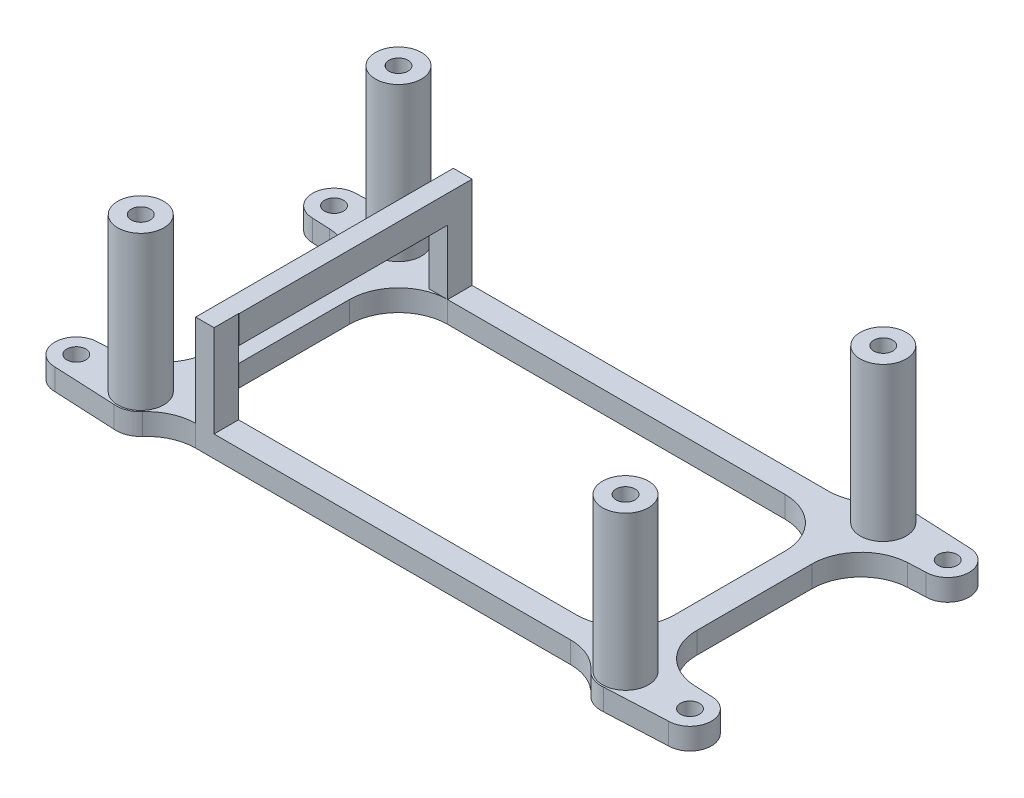
SolidWorks part; units mm, degrees
ref_plane "Front Plane" through (0, 0, 0) normal (0, 0, 1) x (1, 0, 0)
ref_plane "Top Plane" through (0, 0, 0) normal (0, 1, 0) x (1, 0, 0)
ref_plane "Right Plane" through (0, 0, 0) normal (1, 0, 0) x (0, 0, -1)
sketch "Sketch10" plane through (0, 0, 0) normal (0, 1, 0) x (1, 0, 0)
  line L0 (39.5, 0) -> (39.5, -21) construction
  line L1 (0, 0) -> (79, 0)
  line L2 (0, 0) -> (0, -42)
  line L3 (0, -42) -> (79, -42)
  line L4 (79, 0) -> (79, -42)
  line L5 (4, -38) -> (75, -38)
  line L6 (4, -38) -> (4, -4)
  line L7 (4, -4) -> (75, -4)
  line L8 (75, -38) -> (75, -4)
  line L9 (4, -38) -> (75, -4) construction
  line L10 (4, -4) -> (75, -38) construction
  line L11 (-10.5, 3.5) -> (0, 4)
  line L12 (-10.5, -3.5) -> (0, -4)
  line L13 (-10.5, -38.5) -> (0, -38)
  line L14 (-10.5, -45.5) -> (0, -46)
  line L15 (89.5, 3.5) -> (79, 4)
  line L16 (89.5, -3.5) -> (79, -4)
  line L17 (89.5, -38.5) -> (79, -38)
  line L18 (89.5, -45.5) -> (79, -46)
  circle A0 centre (0, 0) radius 4
  circle A1 centre (79, 0) radius 4
  circle A2 centre (79, -42) radius 4
  circle A3 centre (0, -42) radius 4
  circle A4 centre (-10.5, 0) radius 3.5
  circle A5 centre (-10.5, -42) radius 3.5
  circle A6 centre (89.5, 0) radius 3.5
  circle A7 centre (89.5, -42) radius 3.5
  arc A8 (-10.5, 3.5) -> (-10.5, -3.5) centre (-10.5, 0) cw
  arc A9 (0, 4) -> (0, -4) centre (0, 0) ccw
  arc A10 (79, 4) -> (79, -4) centre (79, 0) cw
  arc A11 (79, -38) -> (79, -46) centre (79, -42) cw
  arc A12 (89.5, -38.5) -> (89.5, -45.5) centre (89.5, -42) ccw
  arc A13 (0, -38) -> (0, -46) centre (0, -42) ccw
  arc A14 (-10.5, -38.5) -> (-10.5, -45.5) centre (-10.5, -42) cw
  point P5 (39.5, -21)
  point P10 (39.5, 0)
  point P11 (0, -21)
  dimension "D3" = 79
  dimension "D4" = 42
  dimension "D5" = 8
  dimension "D6" = 7
  dimension "D1" = 4
  dimension "D2" = 4
  dimension "D7" = 100
extrude "Boss-Extrude6" add sketch "Sketch10" along normal blind 3.5 contours A3 L3 A2 L4 A1 L1 A0 L2 L8 L5 L6 L7 | L1 A0 L11 L12 L2 | L2 A0 L1 | L3 A3 L2 | L1 A1 L4 | L18 A2 L17 L4 L3 | L16 A1 L15 L1 L4 | A5 L14 A3 L13 | A5 | A7 | A7 L17 A2 L18 | L4 A2 L3 | A6 | A6 L15 A1 L16 | A4 L12 A0 L11 | A4
sketch "Sketch11" plane through (0, 3.5, 0) normal (0, 1, 0) x (1, 0, 0)
  circle A0 centre (0, 0) radius 1.55
  circle A1 centre (79, 0) radius 1.55
  circle A2 centre (79, -42) radius 1.55
  circle A3 centre (0, -42) radius 1.55
  circle A4 centre (-10.5, -42) radius 1.55
  circle A5 centre (-10.5, 0) radius 1.55
  circle A6 centre (89.5, 0) radius 1.55
  circle A7 centre (89.5, -42) radius 1.55
  dimension "D1" = 3.1
  dimension "D2" = 3.1
extrude "Cut-Extrude6" cut sketch "Sketch11" against normal up to surface (3.5 mm away) up to face at (41.6252, 0, 22.709)
sketch "Sketch12" plane through (0, 0, 0) normal (0, -1, 0) x (1, 0, 0)
  circle A0 centre (0, 42) radius 2.75
  circle A1 centre (79, 42) radius 2.75
  circle A2 centre (79, 0) radius 2.75
  circle A3 centre (0, 0) radius 2.75
  dimension "D1" = 5.5
extrude "Cut-Extrude7" cut sketch "Sketch12" against normal blind 3.5
sketch "Sketch13" plane through (0, 3.5, 0) normal (0, 1, 0) x (1, 0, 0)
  circle A0 centre (0, 0) radius 3.75
  circle A1 centre (79, 0) radius 3.75
  circle A2 centre (79, -42) radius 3.75
  circle A3 centre (0, -42) radius 3.75
  dimension "D1" = 7.5
extrude "Boss-Extrude7" add sketch "Sketch13" along normal blind 25
sketch "Sketch14" plane through (0, 28.5, 0) normal (0, 1, 0) x (1, 0, 0)
  circle A0 centre (0, 0) radius 1.55
  circle A1 centre (79, 0) radius 1.55
  circle A2 centre (79, -42) radius 1.55
  circle A3 centre (0, -42) radius 1.55
  dimension "D1" = 3.1
extrude "Cut-Extrude8" cut sketch "Sketch14" against normal through all both and the other way through all
fillet "Fillet6" radius 8 8 edges at (75, 1.75, 0) (4, 1.75, 0) (4, 1.75, 42) (75, 1.75, 42) (79, 1.75, 4) (0, 1.75, 38) (0, 1.75, 4)
fillet "Fillet7" radius 8 4 edges at (75, 1.75, 38) (4, 1.75, 38) (75, 1.75, 4) (4, 1.75, 4)
sketch "Sketch16" plane through (0, 3.5, 0) normal (0, 1, 0) x (1, 0, 0)
  line L11 (12, -38) -> (67, -38) construction
  line L12 (8.9443, -42) -> (11.9443, -42)
  line L13 (8.9443, -42) -> (8.9443, -38)
  line L14 (8.9443, -38) -> (11.9443, -38)
  line L15 (11.9443, -42) -> (11.9443, -38)
  line L17 (12, -4) -> (8.9443, -4)
  line L18 (12, -4) -> (12, 0)
  line L19 (12, 0) -> (8.9443, 0)
  line L20 (8.9443, -4) -> (8.9443, 0)
  dimension "D1" = 3
extrude "Boss-Extrude10" add sketch "Sketch16" along normal blind 15
sketch "Sketch18" plane through (0, 0, 4) normal (0, 0, 1) x (1, 0, 0)
  line L0 (12, 18.5) -> (12, 3.5) construction
  line L1 (8.9443, 18.5) -> (12, 18.5)
  line L2 (8.9443, 18.5) -> (8.9443, 14)
  line L3 (8.9443, 14) -> (12, 14)
  line L4 (12, 18.5) -> (12, 14)
  dimension "D1" = 4.5
extrude "Boss-Extrude11" add sketch "Sketch18" along normal up to surface (34 mm away) up to face at (10.4443, 11, 38)
